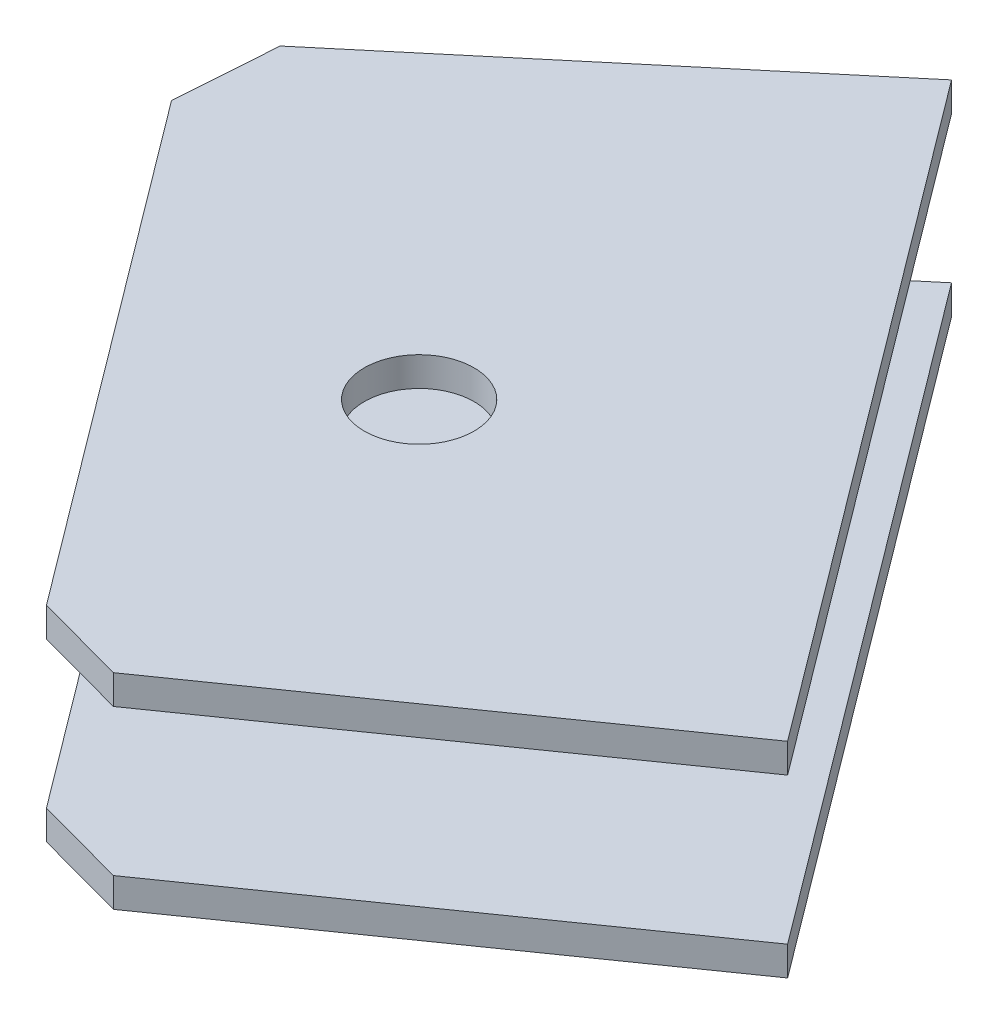
SolidWorks part; units mm, degrees
ref_plane "Front Plane" through (0, 0, 0) normal (0, 0, 1) x (1, 0, 0)
ref_plane "Top Plane" through (0, 0, 0) normal (0, 1, 0) x (1, 0, 0)
ref_plane "Right Plane" through (0, 0, 0) normal (1, 0, 0) x (0, 0, -1)
sketch "Sketch1" plane through (0, 0, 0) normal (0, 1, 0) x (1, 0, 0)
  line L0 (-33.1949, 11.7162) -> (2.8994, 42.003)
  line L1 (-33.1949, 11.7162) -> (242.7216, 243.2377) construction
  line L2 (2.8994, 42.003) -> (37.8448, -4.6144)
  line L4 (37.8448, -4.6144) -> (-0.714, -31.6136)
  line L5 (-0.714, -31.6136) -> (-33.1949, 11.7162)
  line L6 (242.7216, 138.8419) -> (-0.714, -31.6136) construction
  circle A1 centre (0, 0) radius 6.35
ref_plane "Plane1" through (0, 6.35, 0) normal (0, 1, 0) x (-1, 0, 0)
ref_plane "Plane2" through (0, -6.35, 0) normal (0, 1, 0) x (-1, 0, 0)
sketch "Sketch2" plane through (0, 6.35, 0) normal (0, 1, 0) x (-1, 0, 0)
  line L14 (33.1949, -11.7162) -> (0.714, 31.6136) construction
  line L15 (-41.6555, 9.698) -> (-50.5774, 21.5998) construction
  line L16 (-41.6555, 9.698) -> (0.9151, -47.0916)
  line L17 (0.714, 31.6136) -> (33.1949, -11.7162)
  line L18 (-46.8599, 6.0539) -> (-3.9566, -51.1794)
  line L19 (-3.9566, -51.1794) -> (41.8811, -12.717)
  line L20 (41.8811, -12.717) -> (2.1076, 40.3413)
  line L21 (2.1076, 40.3413) -> (-46.8599, 6.0539)
  line L22 (33.1949, -11.7162) -> (32.5773, -20.5238)
  line L23 (0.9151, -47.0916) -> (32.5773, -20.5238)
  line L24 (0.714, 31.6136) -> (-7.2588, 33.7829)
  line L25 (-7.2588, 33.7829) -> (-41.6555, 9.698)
  circle A0 centre (0, 0) radius 4.7625
  dimension "D1" = 6.35
extrude "Boss-Extrude1" add sketch "Sketch2" along normal blind 2.54
sketch "Sketch3" plane through (0, -6.35, 0) normal (0, 1, 0) x (-1, 0, 0)
  line L4 (-7.2588, 33.7829) -> (-41.6555, 9.698)
  line L5 (-41.6555, 9.698) -> (0.9151, -47.0916)
  line L6 (0.9151, -47.0916) -> (32.5773, -20.5238)
  line L7 (33.1949, -11.7162) -> (0.714, 31.6136)
  line L8 (-7.2588, 33.7829) -> (-41.6555, 9.698)
  line L9 (-41.6555, 9.698) -> (0.9151, -47.0916)
  line L10 (0.9151, -47.0916) -> (32.5773, -20.5238)
  line L11 (33.1949, -11.7162) -> (0.714, 31.6136)
  line L14 (32.5773, -20.5238) -> (33.1949, -11.7162)
  line L15 (32.5773, -20.5238) -> (33.1949, -11.7162)
  line L16 (0.714, 31.6136) -> (-7.2588, 33.7829)
  line L17 (0.714, 31.6136) -> (-7.2588, 33.7829)
  circle A0 centre (0, 0) radius 4.7625 construction
  circle A1 centre (0, 0) radius 4.7625
  dimension "D1" = 0
extrude "Boss-Extrude2" add sketch "Sketch3" against normal blind 2.54 separate body
